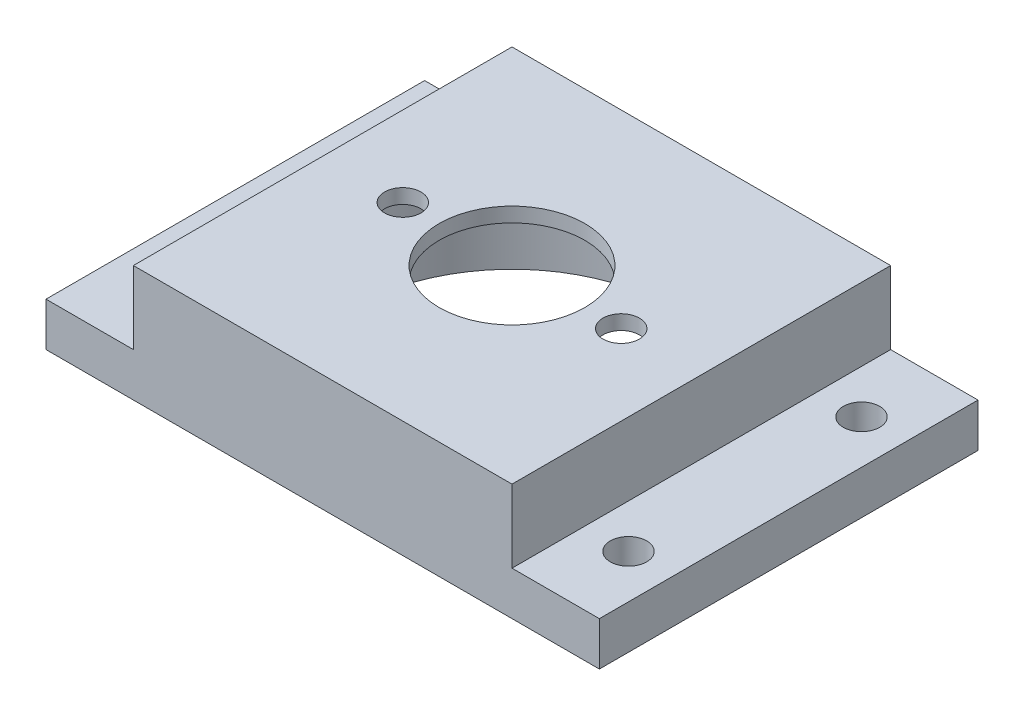
SolidWorks part; units mm, degrees
ref_plane "Front" through (0, 0, 0) normal (0, 0, 1) x (1, 0, 0)
ref_plane "Top" through (0, 0, 0) normal (0, 1, 0) x (1, 0, 0)
ref_plane "Right" through (0, 0, 0) normal (1, 0, 0) x (0, 0, -1)
sketch "Sketch1" plane through (0, 0, 0) normal (0, 0, 1) x (1, 0, 0)
  line L0 (0, 0) -> (8, 0)
  line L4 (30, 0) -> (38, 0)
  line L5 (38, 0) -> (38, 3)
  line L6 (38, 3) -> (32, 3)
  line L7 (32, 3) -> (32, 8)
  line L8 (32, 8) -> (6, 8)
  line L9 (6, 8) -> (6, 3)
  line L10 (6, 3) -> (0, 3)
  line L11 (0, 3) -> (0, 0)
  line L12 (8, 0) -> (30, 0)
  dimension "D1" = 38
  dimension "D2" = 3
  dimension "D4" = 8
  dimension "D7" = 6
  dimension "D9" = 6
extrude "Boss-Extrude1" add sketch "Sketch1" along normal blind 26
sketch "Sketch2" plane through (0, 8, 0) normal (0, 1, 0) x (1, 0, 0)
  line L0 (19, -26) -> (19, 0) construction
  line L1 (32, -26) -> (6, -26) construction
  line L2 (32, 0) -> (6, 0) construction
  line L3 (19, -13) -> (10.0968, -13) construction
  line L4 (6, -26) -> (0, -26) construction
  circle A0 centre (19, -13) radius 5
  circle A1 centre (11.5, -13) radius 1.25
  circle A2 centre (26.5, -13) radius 1.25
  circle A3 centre (3, -21) radius 1.25
  circle A4 centre (3, -5) radius 1.25
  circle A5 centre (35, -21) radius 1.25
  circle A6 centre (35, -5) radius 1.25
  circle A7 centre (19, -13) radius 7.5 construction
  dimension "D1" = 10
  dimension "D4" = 2.5
  dimension "D5" = 16
  dimension "D6" = 5
  dimension "D8" = 16
  dimension "D9" = 15
  dimension "D7" = 16
extrude "Cut-Extrude1" cut sketch "Sketch2" against normal through all
sketch "Sketch3" plane through (0, 0, 0) normal (0, -1, 0) x (1, 0, 0)
  circle A0 centre (19, 13) radius 11
  dimension "D1" = 22
extrude "Cut-Extrude2" cut sketch "Sketch3" against normal blind 7
sketch "Sketch5" plane through (0, 0, 0) normal (0, 0, -1) x (-1, 0, 0)
  line L0 (0, 0) -> (-38, 0) construction
  line L1 (-29, 2.5) -> (-9, 2.5) construction
  line L2 (-19, 8) -> (-19, 2.5) construction
  line L3 (-32, 8) -> (-6, 8) construction
  circle A0 centre (-29, 2.5) radius 1
  circle A1 centre (-9, 2.5) radius 1
  dimension "D3" = 2
  dimension "D1" = 2.5
  dimension "D2" = 20
extrude "Cut-Extrude7" cut sketch "Sketch5" against normal blind 6
